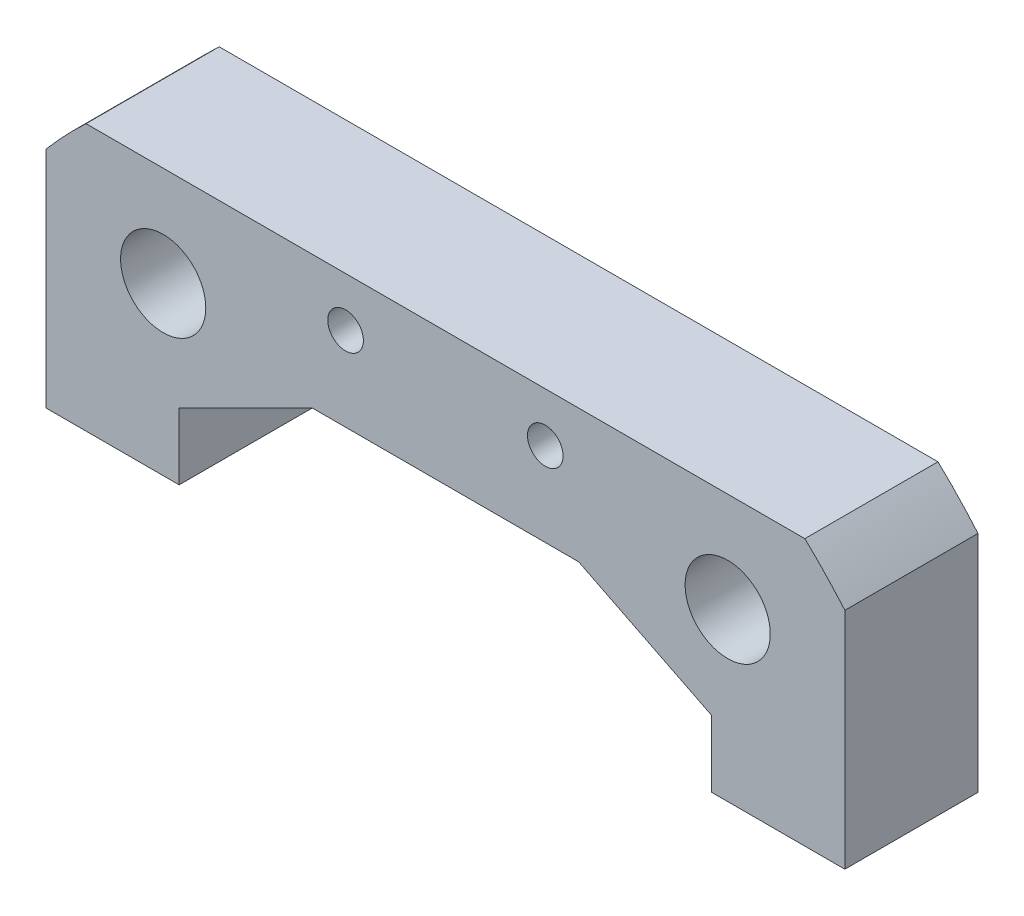
SolidWorks part; units mm, degrees
ref_plane "Front Plane" through (0, 0, 0) normal (0, 0, 1) x (1, 0, 0)
ref_plane "Top Plane" through (0, 0, 0) normal (0, 1, 0) x (1, 0, 0)
ref_plane "Right Plane" through (0, 0, 0) normal (1, 0, 0) x (0, 0, -1)
sketch "Sketch1" plane through (0, 0, 0) normal (0, 0, 1) x (1, 0, 0)
  line L0 (0, 0) -> (-38.1, 0)
  line L1 (-38.1, 0) -> (-38.1, -25.4)
  line L2 (-38.1, -25.4) -> (-25.4, -25.4)
  line L3 (-25.4, -25.4) -> (-25.4, -19.05)
  line L4 (-25.4, -19.05) -> (-12.7, -12.7)
  line L5 (-12.7, -12.7) -> (0, -12.7)
  line L6 (0, -12.7) -> (0, 0)
  circle A0 centre (-26.924, -9.525) radius 4.064
  dimension "D7" = 26.924
  dimension "D8" = 9.525
  dimension "D9" = 8.128
  dimension "D1" = 25.4
  dimension "D2" = 12.7
  dimension "D3" = 12.7
  dimension "D4" = 6.35
  dimension "D5" = 38.1
  dimension "D6" = 12.7
extrude "Boss-Extrude1" add sketch "Sketch1" along normal blind 12.7
mirror "Mirror1" about plane through (0, -12.7, 12.7) normal (-1, 0, 0) of "Boss-Extrude1"
sketch "Sketch2" plane through (0, 0, 12.7) normal (0, 0, 1) x (1, 0, 0)
  line L1 (-38.1, 0) -> (-38.1, -25.4) construction
  line L4 (38.1, 0) -> (38.1, -25.4) construction
  line L12 (-38.1, -4.0115) -> (-38.1, 0)
  line L13 (-38.1, 0) -> (-34.2822, 0)
  line L14 (38.1, 0) -> (-38.1, 0) construction
  line L15 (34.2822, 0) -> (38.1, 0)
  line L16 (38.1, 0) -> (38.1, -4.0115)
  arc A0 (38.1, -4.0115) -> (34.2822, 0) centre (0, -36.449) ccw construction
  circle A1 centre (-26.924, -9.525) radius 4.064 construction
  arc A3 (38.1, -4.0115) -> (34.2822, 0) centre (0, -36.449) ccw construction
  arc A4 (38.1, -4.0115) -> (34.2822, 0) centre (0, -36.449) ccw
  circle A5 centre (-9.525, -4.699) radius 1.7
  circle A6 centre (9.525, -4.699) radius 1.7
  arc A7 (-34.2822, 0) -> (-38.1, -4.0115) centre (0, -36.449) ccw construction
  arc A9 (-34.2822, 0) -> (-38.1, -4.0115) centre (0, -36.449) ccw construction
  arc A10 (-34.2822, 0) -> (-38.1, -4.0115) centre (0, -36.449) ccw
  point P1 (38.1, -4.0115)
  dimension "D2" = 26.924
  dimension "D3" = 100.076
  dimension "D5" = 31.75
  dimension "D6" = 9.525
  dimension "D7" = 3.4
  dimension "D8" = 3.4
  dimension "D9" = 9.525
  dimension "D10" = 31.75
  dimension "D1" = 26.924
extrude "Cut-Extrude1" cut sketch "Sketch2" against normal through all
fillet "Fillet1" [suppressed] radius 3.175
